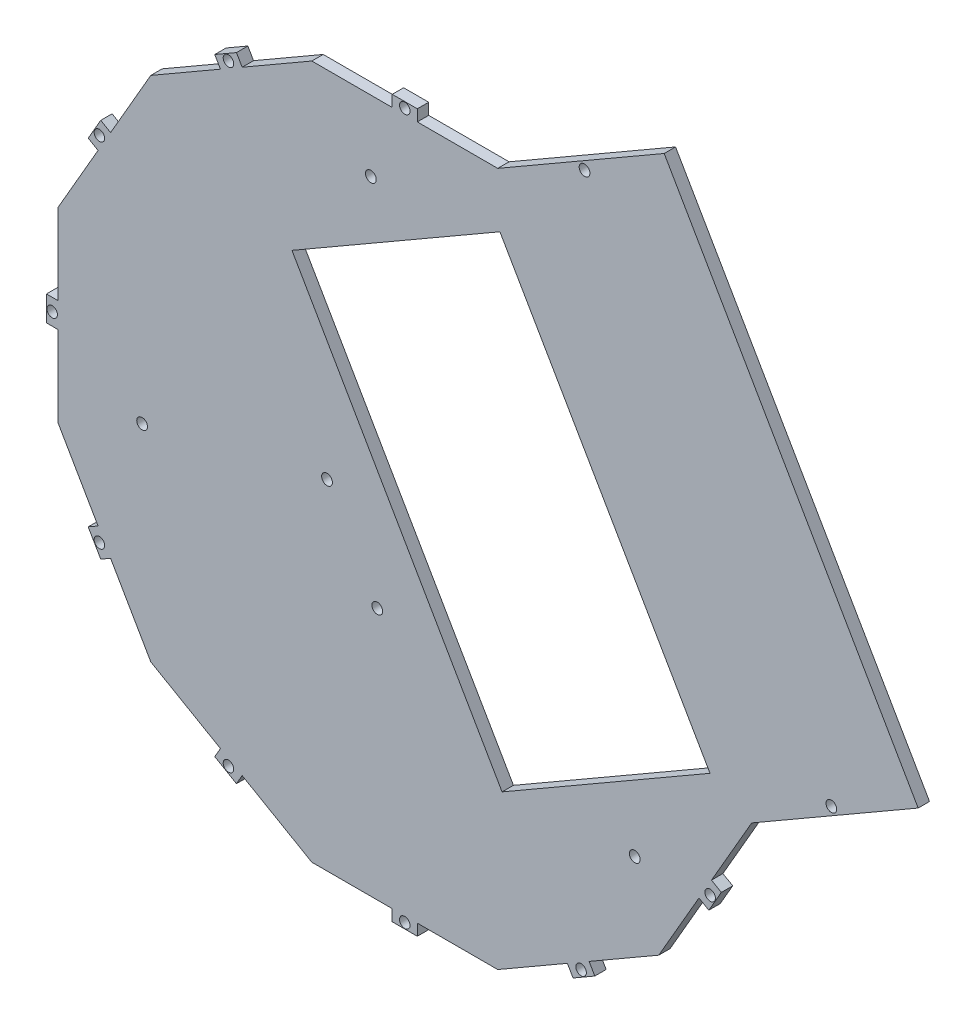
SolidWorks part; units mm, degrees
ref_plane "Front Plane" through (0, 0, 0) normal (0, 0, 1) x (1, 0, 0)
ref_plane "Top Plane" through (0, 0, 0) normal (0, 1, 0) x (1, 0, 0)
ref_plane "Right Plane" through (0, 0, 0) normal (1, 0, 0) x (0, 0, -1)
sketch "Sketch1" plane through (0, 0, 0) normal (0, 0, 1) x (1, 0, 0)
  line L0 (0, 0) -> (0, 154.0689) construction
  line L1 (0, 0) -> (238.7074, 0) construction
  line L2 (-26.7949, 100) -> (26.7949, 100)
  line L3 (0, 0) -> (0, -151.6118) construction
  line L4 (-26.7949, -100) -> (26.7949, -100)
  line L5 (0, 0) -> (-184.5569, 0) construction
  line L6 (-100, 26.7949) -> (-100, -26.7949)
  line L12 (0, 0) -> (-101.5418, 101.5418) construction
  line L13 (-100, 26.7949) -> (-73.2051, 73.2051)
  line L14 (-73.2051, 73.2051) -> (-26.7949, 100)
  line L15 (-100, -26.7949) -> (-73.2051, -73.2051)
  line L16 (-73.2051, -73.2051) -> (-26.7949, -100)
  line L17 (73.2051, -73.2051) -> (26.7949, -100)
  line L18 (100, -26.7949) -> (73.2051, -73.2051)
  line L20 (100, 26.7949) -> (73.2051, 73.2051)
  line L21 (73.2051, 73.2051) -> (26.7949, 100)
  line L22 (100, -26.7949) -> (100, 26.7949)
  point P17 (0, -100)
  point P22 (0, 100)
  dimension "D1" = 200
  dimension "D2" = 200
  dimension "D3" = 150
  dimension "D4" = 150
  dimension "D5" = 150
extrude "Boss-Extrude1" add sketch "Sketch1" along normal blind 3.175
sketch "Sketch3" plane through (0, 0, 0) normal (0, 0, -1) x (-1, 0, 0)
  line L0 (50, -86.6025) -> (0, 0) construction
  line L1 (73.2051, -73.2051) -> (26.7949, -100) construction
  line L2 (53.0311, -84.8525) -> (51.4436, -82.1029)
  line L3 (51.4436, -82.1029) -> (70.8808, -70.8808)
  line L5 (73.2051, -73.2051) -> (53.0311, -84.8525)
  line L6 (73.2051, -73.2051) -> (69.2709, -69.2709) construction
  line L7 (52.2373, -83.4777) -> (46.9797, -86.5132) construction
  line L8 (26.7949, -100) -> (46.9689, -88.3525)
  line L9 (46.9689, -88.3525) -> (45.3814, -85.6029)
  line L10 (45.3814, -85.6029) -> (25.9442, -96.825)
  line L11 (3.5, -96.825) -> (25.9442, -96.825)
  line L12 (3.5, -100) -> (3.5, -96.825)
  line L13 (26.7949, -100) -> (3.5, -100)
  line L14 (-3.5, -96.825) -> (-25.9442, -96.825)
  line L15 (-3.5, -100) -> (-3.5, -96.825)
  line L16 (-26.7949, -100) -> (-3.5, -100)
  line L17 (-45.3814, -85.6029) -> (-25.9442, -96.825)
  line L18 (-46.9689, -88.3525) -> (-45.3814, -85.6029)
  line L19 (-26.7949, -100) -> (-46.9689, -88.3525)
  line L20 (-51.4436, -82.1029) -> (-70.8808, -70.8808)
  line L21 (-53.0311, -84.8525) -> (-51.4436, -82.1029)
  line L22 (-73.2051, -73.2051) -> (-53.0311, -84.8525)
  line L23 (-82.1029, -51.4436) -> (-70.8808, -70.8808)
  line L24 (-84.8525, -53.0311) -> (-82.1029, -51.4436)
  line L25 (-73.2051, -73.2051) -> (-84.8525, -53.0311)
  line L26 (-85.6029, -45.3814) -> (-96.825, -25.9442)
  line L27 (-88.3525, -46.9689) -> (-85.6029, -45.3814)
  line L28 (-100, -26.7949) -> (-88.3525, -46.9689)
  line L29 (-96.825, -3.5) -> (-96.825, -25.9442)
  line L30 (-100, -3.5) -> (-96.825, -3.5)
  line L31 (-100, -26.7949) -> (-100, -3.5)
  line L32 (-96.825, 3.5) -> (-96.825, 25.9442)
  line L33 (-100, 3.5) -> (-96.825, 3.5)
  line L34 (-100, 26.7949) -> (-100, 3.5)
  line L35 (-85.6029, 45.3814) -> (-96.825, 25.9442)
  line L36 (-88.3525, 46.9689) -> (-85.6029, 45.3814)
  line L37 (-100, 26.7949) -> (-88.3525, 46.9689)
  line L38 (-82.1029, 51.4436) -> (-70.8808, 70.8808)
  line L39 (-84.8525, 53.0311) -> (-82.1029, 51.4436)
  line L40 (-73.2051, 73.2051) -> (-84.8525, 53.0311)
  line L41 (-51.4436, 82.1029) -> (-70.8808, 70.8808)
  line L42 (-53.0311, 84.8525) -> (-51.4436, 82.1029)
  line L43 (-73.2051, 73.2051) -> (-53.0311, 84.8525)
  line L44 (-45.3814, 85.6029) -> (-25.9442, 96.825)
  line L45 (-46.9689, 88.3525) -> (-45.3814, 85.6029)
  line L46 (-26.7949, 100) -> (-46.9689, 88.3525)
  line L47 (-3.5, 96.825) -> (-25.9442, 96.825)
  line L48 (-3.5, 100) -> (-3.5, 96.825)
  line L49 (-26.7949, 100) -> (-3.5, 100)
  line L50 (3.5, 96.825) -> (25.9442, 96.825)
  line L51 (3.5, 100) -> (3.5, 96.825)
  line L52 (26.7949, 100) -> (3.5, 100)
  line L53 (45.3814, 85.6029) -> (25.9442, 96.825)
  line L54 (46.9689, 88.3525) -> (45.3814, 85.6029)
  line L55 (26.7949, 100) -> (46.9689, 88.3525)
  line L56 (51.4436, 82.1029) -> (70.8808, 70.8808)
  line L57 (53.0311, 84.8525) -> (51.4436, 82.1029)
  line L58 (73.2051, 73.2051) -> (53.0311, 84.8525)
  line L59 (82.1029, 51.4436) -> (70.8808, 70.8808)
  line L60 (84.8525, 53.0311) -> (82.1029, 51.4436)
  line L61 (73.2051, 73.2051) -> (84.8525, 53.0311)
  line L62 (85.6029, 45.3814) -> (96.825, 25.9442)
  line L63 (88.3525, 46.9689) -> (85.6029, 45.3814)
  line L64 (100, 26.7949) -> (88.3525, 46.9689)
  line L65 (96.825, 3.5) -> (96.825, 25.9442)
  line L66 (100, 3.5) -> (96.825, 3.5)
  line L67 (100, 26.7949) -> (100, 3.5)
  line L68 (96.825, -3.5) -> (96.825, -25.9442)
  line L69 (100, -3.5) -> (96.825, -3.5)
  line L70 (100, -26.7949) -> (100, -3.5)
  line L71 (85.6029, -45.3814) -> (96.825, -25.9442)
  line L72 (88.3525, -46.9689) -> (85.6029, -45.3814)
  line L73 (100, -26.7949) -> (88.3525, -46.9689)
  line L74 (82.1029, -51.4436) -> (70.8808, -70.8808)
  line L75 (84.8525, -53.0311) -> (82.1029, -51.4436)
  line L76 (73.2051, -73.2051) -> (84.8525, -53.0311)
  circle A0 centre (49.2063, -85.2277) radius 1.47
  circle A1 centre (0, -98.4125) radius 1.47
  circle A2 centre (-49.2063, -85.2277) radius 1.47
  circle A3 centre (-85.2277, -49.2062) radius 1.47
  circle A4 centre (-98.4125, 0) radius 1.47
  circle A5 centre (-85.2277, 49.2063) radius 1.47
  circle A6 centre (-49.2062, 85.2277) radius 1.47
  circle A7 centre (0, 98.4125) radius 1.47
  circle A8 centre (49.2063, 85.2277) radius 1.47
  circle A9 centre (85.2277, 49.2062) radius 1.47
  circle A10 centre (98.4125, 0) radius 1.47
  circle A11 centre (85.2277, -49.2063) radius 1.47
  point P133 (0, 0)
  line M8 (26.7949, -100) -> (73.2051, -73.2051)
  line M9 (73.2051, -73.2051) -> (100, -26.7949)
  line M11 (100, 26.7949) -> (73.2051, 73.2051)
  line M12 (73.2051, 73.2051) -> (26.7949, 100)
  line M13 (26.7949, 100) -> (-26.7949, 100)
  line M14 (-26.7949, 100) -> (-73.2051, 73.2051)
  line M15 (-73.2051, 73.2051) -> (-100, 26.7949)
  line M16 (-100, 26.7949) -> (-100, -26.7949)
  line M17 (-100, -26.7949) -> (-73.2051, -73.2051)
  line M18 (-73.2051, -73.2051) -> (-26.7949, -100)
  line M19 (-26.7949, -100) -> (26.7949, -100)
  dimension "D4" = 2.94
  dimension "D1" = 75
  dimension "D2" = 3.5
  dimension "D3" = 3.175
  dimension "D5" = 12
extrude "Cut-Extrude5" cut sketch "Sketch3" against normal blind 10 contours L75 L74 L3 L2 M9 M8 | L18 L15 L14 L17 M18 M19 | L24 L21 L20 L23 M17 M18 | A2 | L30 L27 L26 L29 M16 M17 | L36 L33 L32 L35 M15 M16 | L48 L45 L44 L47 M13 M14 | L54 L51 L50 L53 M12 M13 | L60 L57 L56 L59 M11 M12 | A5 | A6 | A7 | A8 | A9 | A10 | L68 L71 L72 L73 L70 L69 | A11 | L10 L11 L12 L13 L8 L9 | A1 | A0 | A3 | A4 | L38 L41 L42 L43 L40 L39 | L64 L63 L62 L65 L66 L67
sketch "Sketch4" plane through (0, 0, 3.175) normal (0, 0, 1) x (1, 0, 0)
  line L1 (27.5317, 99.5746) -> (25.9442, 96.825)
  line L2 (27.5317, 99.5746) -> (73.1906, 73.2134)
  line L3 (53.0311, 84.8525) -> (46.9689, 88.3525) construction
  line L4 (61.4276, 61.334) -> (82.1818, 82.2936) construction
  line L6 (100, 27.8163) -> (73.1906, 73.2134)
  line L7 (100, 27.8163) -> (100, -25.9442)
  line L8 (96.825, -25.9442) -> (25.9442, 96.825)
  line L11 (100, -3.5) -> (100, 3.5) construction
  line L12 (100, -25.9442) -> (96.825, -25.9442)
extrude "Cut-Extrude6" cut sketch "Sketch4" against normal blind 10
sketch "Sketch5" plane through (0, 0, 3.175) normal (0, 0, 1) x (1, 0, 0)
  line L0 (96.825, -25.9442) -> (143.2786, 0.8758)
  line L1 (143.2786, 0.8758) -> (72.3978, 123.645)
  line L2 (72.3978, 123.645) -> (25.9442, 96.825)
  line L3 (25.9442, 96.825) -> (96.825, -25.9442)
  dimension "D1" = 53.64
extrude "Boss-Extrude2" add sketch "Sketch5" against normal blind 3.175
sketch "Sketch7" plane through (0, 0, 0) normal (0, 0, -1) x (-1, 0, 0)
  line L0 (-96.825, -25.9442) -> (-143.2786, 0.8758) construction
  line L1 (-120.0518, -12.5342) -> (-111.4856, 2.303) construction
  line L2 (-107.8382, 62.2604) -> (86.6977, -50.055) construction
  line L3 (-143.2786, 0.8758) -> (-72.3978, 123.645) construction
  circle A0 centre (-119.0518, -10.8021) radius 1.5
  circle A1 centre (-50.171, 108.5029) radius 1.5
  dimension "D1" = 3
  dimension "D2" = 2
extrude "Cut-Extrude7" cut sketch "Sketch7" against normal blind 10
sketch "Sketch9" plane through (0, 0, 0) normal (0, 0, -1) x (-1, 0, 0)
  circle A0 centre (73.3067, -14.5073) radius 1.5
  circle A1 centre (21.7029, -2.1876) radius 1.5
  circle A2 centre (7.6735, -26.3036) radius 1.5
  dimension "D1" = 3
  dimension "D2" = 3
  dimension "D3" = 3
extrude "Cut-Extrude9" cut sketch "Sketch9" against normal blind 10
sketch "Sketch10" plane through (0, 0, 3.175) normal (0, 0, 1) x (1, 0, 0)
  line L0 (27.1428, -50.7765) -> (26.5644, 79.2963) construction
  line L1 (83.0322, -18.5088) -> (-29.325, 47.0285) construction
  line L2 (27.1428, -50.7765) -> (27.1539, -53.2765) construction
  line L3 (83.0322, -18.5088) -> (85.1917, -19.7684) construction
  line L4 (-29.325, 47.0285) -> (-31.4845, 48.2881) construction
  line L5 (26.5644, 79.2963) -> (26.5533, 81.7963) construction
  line L6 (27.1539, -53.2765) -> (85.1917, -19.7684)
  line L7 (27.1539, -53.2765) -> (-31.4845, 48.2881)
  line L8 (85.1917, -19.7684) -> (26.5533, 81.7963)
  line L9 (-31.4845, 48.2881) -> (26.5533, 81.7963)
  arc A0 (25.6247, -49.6117) -> (29.0398, -50.5268) centre (27.7898, -48.3617) ccw construction
  arc A1 (28.0824, 78.1314) -> (24.6674, 79.0465) centre (25.9174, 76.8814) ccw construction
  arc A2 (81.8674, -20.0268) -> (82.7824, -16.6117) centre (80.6174, -17.8617) ccw construction
  arc A3 (-28.1602, 48.5465) -> (-29.0753, 45.1314) centre (-26.9102, 46.3814) ccw construction
  dimension "D1" = 2.5
  dimension "D2" = 2.5
  dimension "D3" = 2.5
  dimension "D4" = 2.5
extrude "Cut-Extrude10" cut sketch "Sketch10" against normal blind 10
sketch "Sketch11" plane through (0, 0, 3.175) normal (0, 0, 1) x (1, 0, 0)
  circle A0 centre (64.1804, -50.3921) radius 1.5
  circle A1 centre (-9.4596, 77.1562) radius 1.5
  dimension "D1" = 3
  dimension "D2" = 3
extrude "Cut-Extrude11" cut sketch "Sketch11" against normal blind 10
